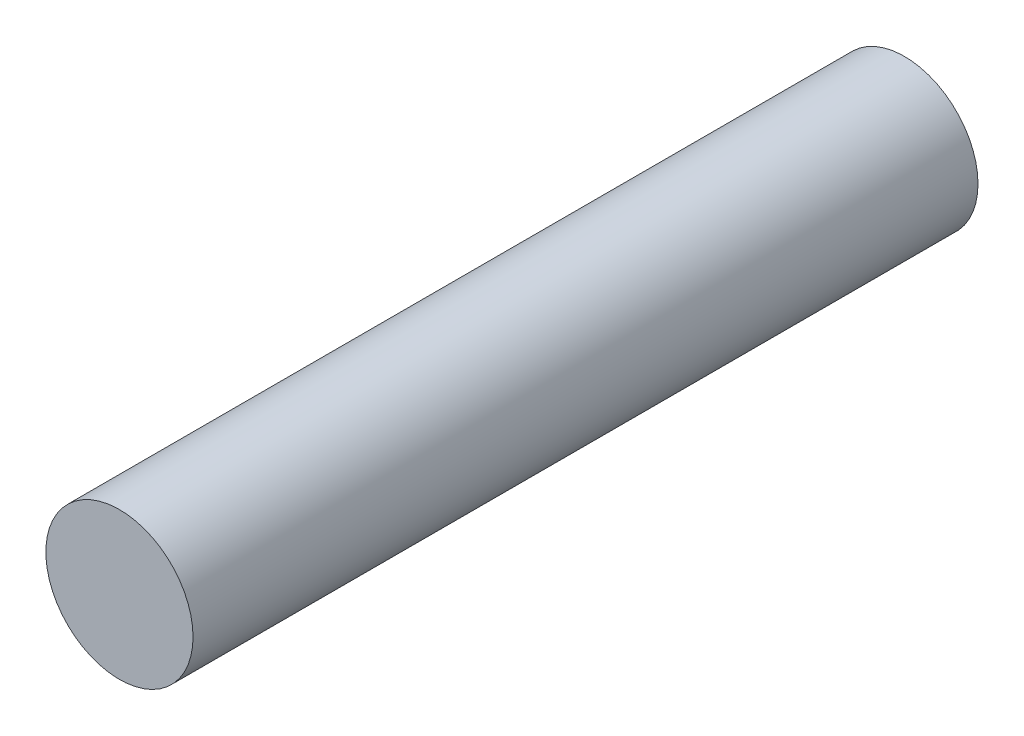
SolidWorks part; units mm, degrees
ref_plane "Front Plane" through (0, 0, 0) normal (0, 0, 1) x (1, 0, 0)
ref_plane "Top Plane" through (0, 0, 0) normal (0, 1, 0) x (1, 0, 0)
ref_plane "Right Plane" through (0, 0, 0) normal (1, 0, 0) x (0, 0, -1)
sketch "Sketch1" plane through (0, 0, 0) normal (0, 0, 1) x (1, 0, 0)
  circle A0 centre (0, 0) radius 7.5
  dimension "D1" = 15
extrude "Boss-Extrude1" add sketch "Sketch1" along normal blind 80
